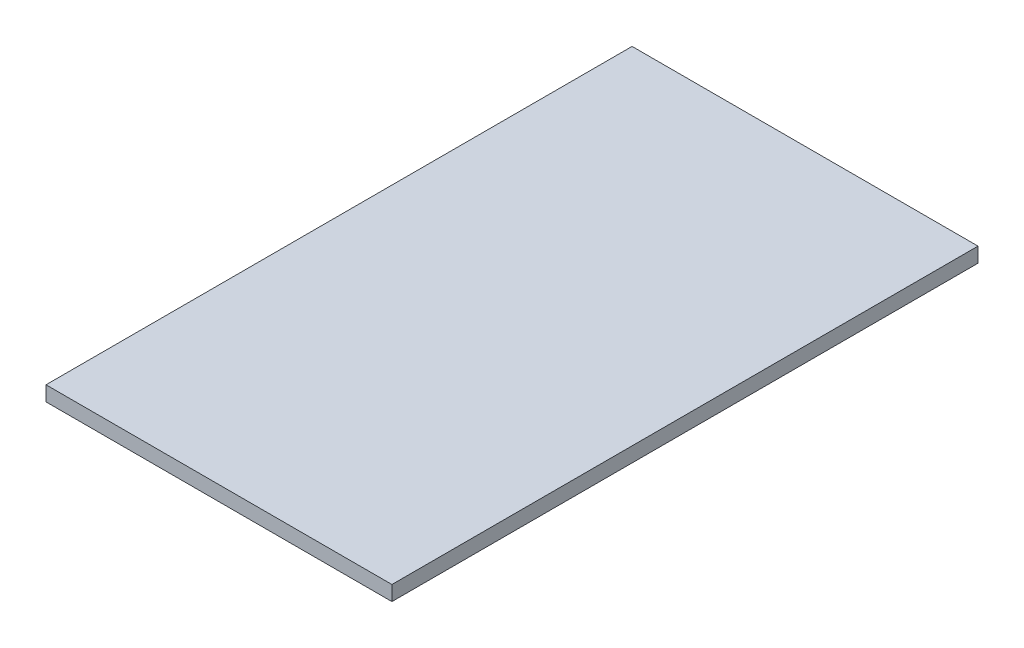
SolidWorks part; units mm, degrees
ref_plane "Front Plane" through (0, 0, 0) normal (0, 0, 1) x (1, 0, 0)
ref_plane "Top Plane" through (0, 0, 0) normal (0, 1, 0) x (1, 0, 0)
ref_plane "Right Plane" through (0, 0, 0) normal (1, 0, 0) x (0, 0, -1)
sketch "草图1" plane through (0, 0, 0) normal (0, 1, 0) x (1, 0, 0)
  line L0 (15, -1387.2) -> (15, -193.6) construction
  line L1 (-20, -193.6) -> (50, -193.6)
  line L3 (-20, 193.6) -> (50, 193.6)
  line L11 (-1100, 0) -> (-130, 0) construction
  line L22 (-20, -193.6) -> (50, -193.6)
  line L25 (-20, 193.6) -> (50, 193.6)
  line L30 (-20, 193.6) -> (-20, -193.6)
  line L31 (-20, -193.6) -> (50, -193.6)
  line L32 (50, 193.6) -> (50, -193.6)
  line L46 (-20, 193.6) -> (50, 193.6)
  line L47 (15, 0) -> (15, 132.8327) construction
  line L48 (-20, 193.6) -> (-20, -193.6)
  line L52 (130, 0) -> (1130, 0) construction
  line L53 (-20, -193.6) -> (50, -193.6)
  point P0 (0, 0)
  point P73 (-50, 173.6)
  dimension "D1" = 70
  dimension "D2" = 387.2
extrude "凸台-拉伸1" add sketch "草图1" along normal blind 3 contours L32 L3 L30 L1
sketch "草图2" plane through (0, 3, 0) normal (0, 1, 0) x (1, 0, 0)
  line L0 (50, -75) -> (-20, -75)
  line L1 (50, 193.6) -> (50, -193.6) construction
  line L2 (-30, -75) -> (250, -75) construction
  line L3 (-20, 193.6) -> (-20, -193.6) construction
  line L4 (-20, -75) -> (-30, -75) construction
  line L6 (50, -75) -> (-34.5334, -75)
  line L7 (50, -75) -> (50, 220.1885)
  line L8 (50, 220.1885) -> (-34.5334, 220.1885)
  line L9 (-34.5334, -75) -> (-34.5334, 220.1885)
  line M5 (50, -193.6) -> (50, 193.6)
  line M6 (50, 193.6) -> (-20, 193.6)
  line M7 (-20, 193.6) -> (-20, -193.6)
extrude "切除-拉伸1" cut sketch "草图2" against normal blind 10 contours L0 M5 M6 M7
